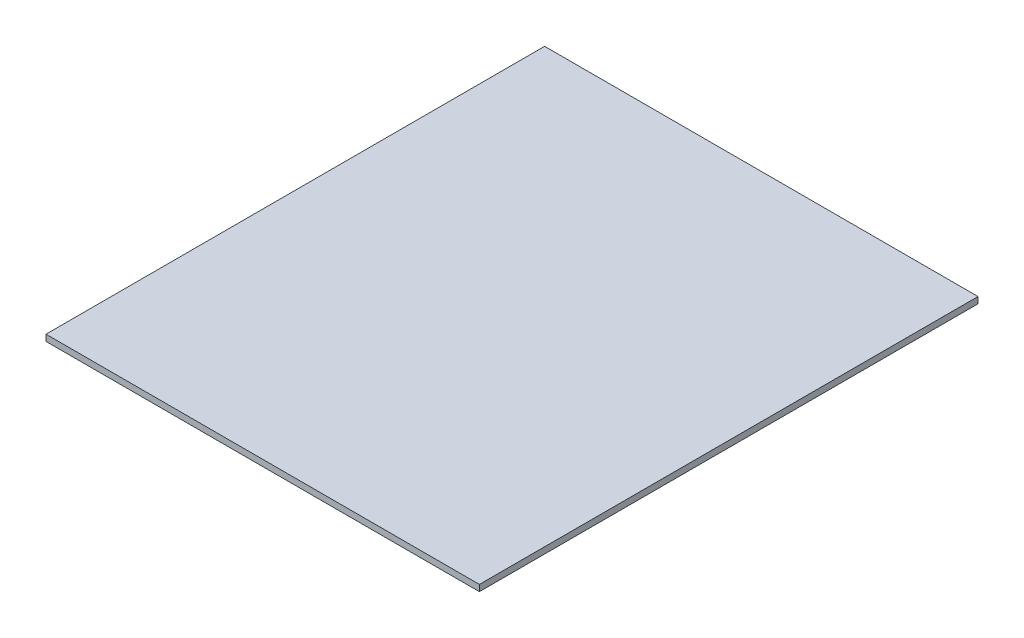
SolidWorks part; units mm, degrees
ref_plane "Front Plane" through (0, 0, 0) normal (0, 0, 1) x (1, 0, 0)
ref_plane "Top Plane" through (0, 0, 0) normal (0, 1, 0) x (1, 0, 0)
ref_plane "Right Plane" through (0, 0, 0) normal (1, 0, 0) x (0, 0, -1)
sketch "Sketch1" plane through (0, 0, 0) normal (0, 1, 0) x (1, 0, 0)
  line L1 (0, 0) -> (206, 0)
  line L2 (0, 0) -> (0, 237)
  line L3 (0, 237) -> (206, 237)
  line L4 (206, 0) -> (206, 237)
  dimension "D1" = 237
  dimension "D2" = 206
extrude "Boss-Extrude1" add sketch "Sketch1" along normal blind 3
